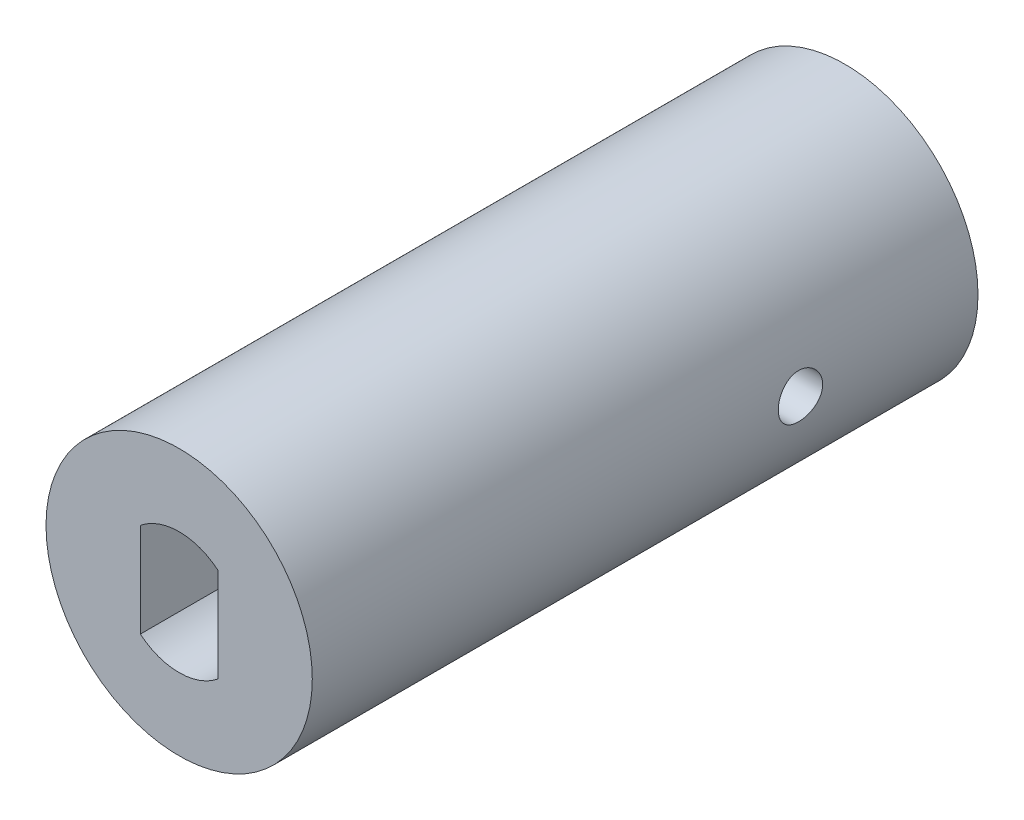
SolidWorks part; units mm, degrees
ref_plane "Alzado" through (0, 0, 0) normal (0, 0, 1) x (1, 0, 0)
ref_plane "Planta" through (0, 0, 0) normal (0, 1, 0) x (1, 0, 0)
ref_plane "Vista lateral" through (0, 0, 0) normal (1, 0, 0) x (0, 0, -1)
sketch "Croquis1" plane through (0, 0, 0) normal (0, 0, 1) x (1, 0, 0)
  circle A0 centre (0, 0) radius 6
  dimension "D1" = 12
extrude "Saliente-Extruir1" add sketch "Croquis1" along normal blind 30
sketch "Croquis2" plane through (0, 0, 0) normal (0, 0, -1) x (-1, 0, 0)
  circle A0 centre (0, 0) radius 4
  dimension "D1" = 8
extrude "Cortar-Extruir1" cut sketch "Croquis2" against normal blind 15
sketch "Croquis3" plane through (0, 0, 30) normal (0, 0, 1) x (1, 0, 0)
  line L1 (-1.75, -2.1213) -> (1.75, -2.1213)
  line L2 (-1.75, -2.1213) -> (-1.75, 2.1213)
  line L3 (-1.75, 2.1213) -> (1.75, 2.1213)
  line L4 (1.75, -2.1213) -> (1.75, 2.1213)
  line L5 (-1.75, -2.1213) -> (1.75, 2.1213) construction
  line L6 (-1.75, 2.1213) -> (1.75, -2.1213) construction
  circle A0 centre (0, 0) radius 2.75
  dimension "D1" = 5.5
  dimension "D2" = 3.5
extrude "Cortar-Extruir2" cut sketch "Croquis3" against normal blind 7 contours L1 L4 L3 L2 | L3 A0 | L1 A0
sketch "Croquis4" plane through (0, 0, 0) normal (1, 0, 0) x (0, 0, -1)
  line L0 (0, -6) -> (0, 6) construction
  circle A0 centre (-8, 0) radius 1
  point P0 (-8, 0)
  dimension "D2" = 2
  dimension "D1" = 8
extrude "Cortar-Extruir3" cut sketch "Croquis4" against normal through all both and the other way through all
